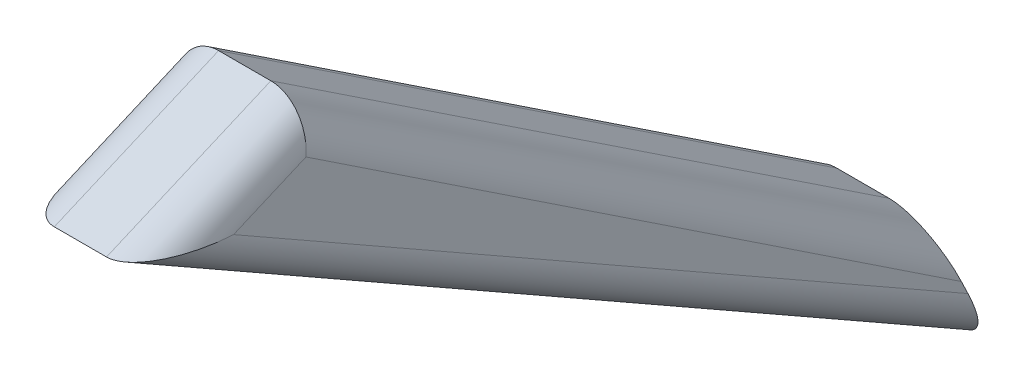
SolidWorks part; units mm, degrees
material "PBT General Purpose"
ref_plane "Front Plane" through (0, 0, 0) normal (0, 0, 1) x (1, 0, 0)
ref_plane "Top Plane" through (0, 0, 0) normal (0, 1, 0) x (1, 0, 0)
ref_plane "Right Plane" through (0, 0, 0) normal (1, 0, 0) x (0, 0, -1)
sketch "Sketch1" plane through (0, 0, 0) normal (1, 0, 0) x (0, 0, -1)
  line L6 (0, 0) -> (0.6291, 0.2696)
  line L7 (0.6291, 0.2696) -> (2.9956, -1.3031)
  line L8 (2.9956, -1.3031) -> (3.2618, -1.8577)
  line L9 (3.2618, -1.8577) -> (0, 0)
  point P3 (0.6291, 0.2696)
extrude "Boss-Extrude1" add sketch "Sketch1" along normal blind 0.5
fillet "Fillet1" radius 0.15 6 edges at (0, -0.9289, -1.6309) (0.5, -0.9289, -1.6309) (0, -0.5167, -1.8123) (0, 0.1348, -0.3145) (0.5, 0.1348, -0.3145) (0.5, -0.5167, -1.8123)
equation "\"t\"= 0.25'thickness of the sheets"
equation "\"t_cf\"= 0.115'thickness of single carbon fiber layer"
equation "\"t_kapton\"= 0.025'thickness of single Kapton flex layer"
equation "\"t_fr4\"= 0.1'thickness of FR4 with copper layer"
equation "\"joint_flex\"= 0.1'Width of flextures gap"
equation "\"joint_flex_eff\"= 0.02'Width of flecture after castelation"
equation "\"joint_fold\"= 0.2'Width of folding joints for 90deg fold"
equation "\"gap_tolerance\"= 0.002'Width to have interfecence fit between carbon fiber inserts"
equation "\"assemble_angle\"= 90'Angle of assembly parts"
equation "\"link_lift\"= 0.5'Actuation linkage amplification for the lift motion"
equation "\"link_swing\"= 0.45'Actuation linkage amplification for the swing motion"
